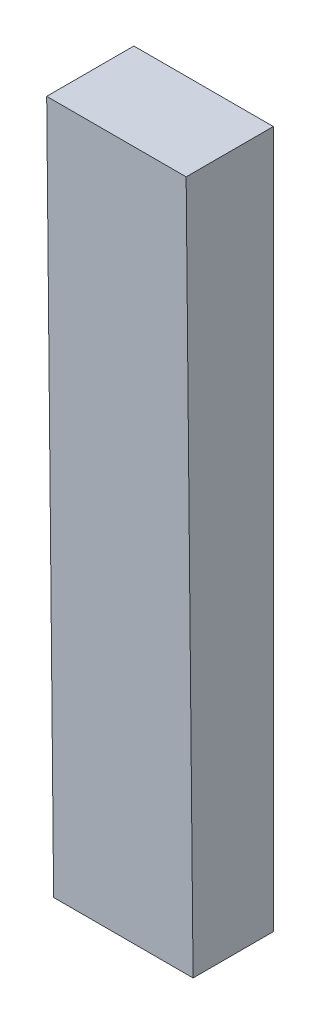
SolidWorks part; units mm, degrees
material "Plain Carbon Steel"
ref_plane "Front Plane" through (0, 0, 0) normal (1, 0, 0) x (0, 1, 0)
ref_plane "Top Plane" through (0, 0, 0) normal (0, 0, 1) x (0, 1, 0)
ref_plane "Right Plane" through (0, 0, 0) normal (0, 1, 0) x (-1, 0, 0)
sketch "Sketch1" plane through (0, 0, 0) normal (1, 0, 0) x (0, 1, 0)
  line L0 (0, 0) -> (-160, 0)
  line L1 (-160, 0) -> (-160, 18.4082)
  line L2 (-160, 18.4082) -> (0, 20)
  line L3 (0, 20) -> (0, 0)
  line L4 (0, 20) -> (-129.4437, 20) construction
  point P3 (-160, 8.4179)
  dimension "D1" = 160
  dimension "D2" = 20
  dimension "D3" = 0.57
extrude "Boss-Extrude1" add sketch "Sketch1" along normal blind 32
